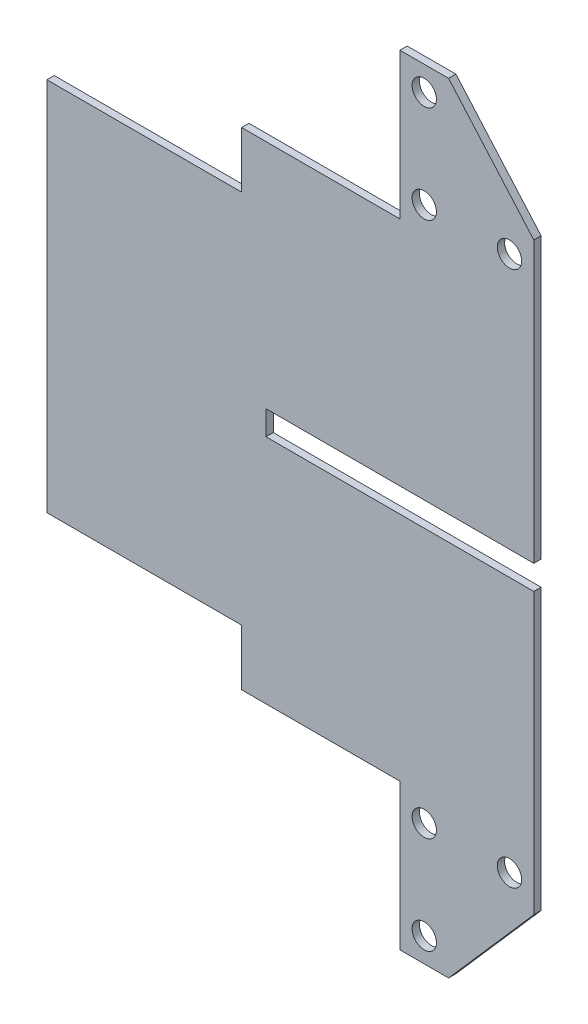
SolidWorks part; units mm, degrees
ref_plane "Plan de face" through (0, 0, 0) normal (0, 0, 1) x (1, 0, 0)
ref_plane "Plan de dessus" through (0, 0, 0) normal (0, 1, 0) x (1, 0, 0)
ref_plane "Plan de droite" through (0, 0, 0) normal (1, 0, 0) x (0, 0, -1)
sketch "Esquisse1" plane through (0, 0, 0) normal (0, 0, 1) x (1, 0, 0)
  line L1 (0, 100) -> (200, 100)
  line L2 (0, 100) -> (0, 0)
  line L3 (0, 0) -> (200, 0)
  line L4 (200, 100) -> (200, 0)
  line L5 (0, 100) -> (55, 100)
  line L7 (0, 100) -> (80, 100)
  line L8 (0, 100) -> (0, 77)
  line L9 (200, 100) -> (145, 100)
  line L10 (200, 100) -> (200, 160)
  line L11 (200, 160) -> (145, 160)
  line L12 (145, 100) -> (145, 160)
  line L13 (200, 0) -> (90, 0)
  line L14 (200, 0) -> (200, 5)
  line L15 (200, 5) -> (90, 5)
  line L16 (90, 0) -> (90, 5)
  line L18 (200, 100) -> (200, 83.1506)
  line L21 (200, 120) -> (180, 120) construction
  line L22 (180, 120) -> (180, 100) construction
  line L23 (180, 120) -> (200, 100) construction
  line L24 (0, 77) -> (80, 77)
  line L25 (80, 100) -> (80, 77)
  line L32 (165, 160) -> (165, 100) construction
  line L33 (145, 140) -> (165, 140) construction
  line L34 (165, 120) -> (145, 120) construction
  line L35 (145, 160) -> (165, 140) construction
  line L36 (145, 120) -> (165, 100) construction
  line L38 (165, 160) -> (200, 120)
  circle A1 centre (190, 110) radius 5
  circle A5 centre (155, 150) radius 5
  circle A6 centre (155, 110) radius 5
  point P24 (190, 110)
  point P56 (155, 150)
  point P58 (155, 110)
  dimension "D10" = 10
  dimension "D21" = 10
  dimension "D22" = 10
  dimension "D1" = 200
  dimension "D2" = 100
  dimension "D3" = 80
  dimension "D4" = 23
  dimension "D5" = 110
  dimension "D6" = 5
  dimension "D11" = 20
  dimension "D12" = 20
  dimension "D20" = 20
extrude "Boss.-Extru.1" add sketch "Esquisse1" along normal blind 3
mirror "Symétrie1" about plane through (0, 0, 3) normal (0, 1, 0) of "Boss.-Extru.1"
